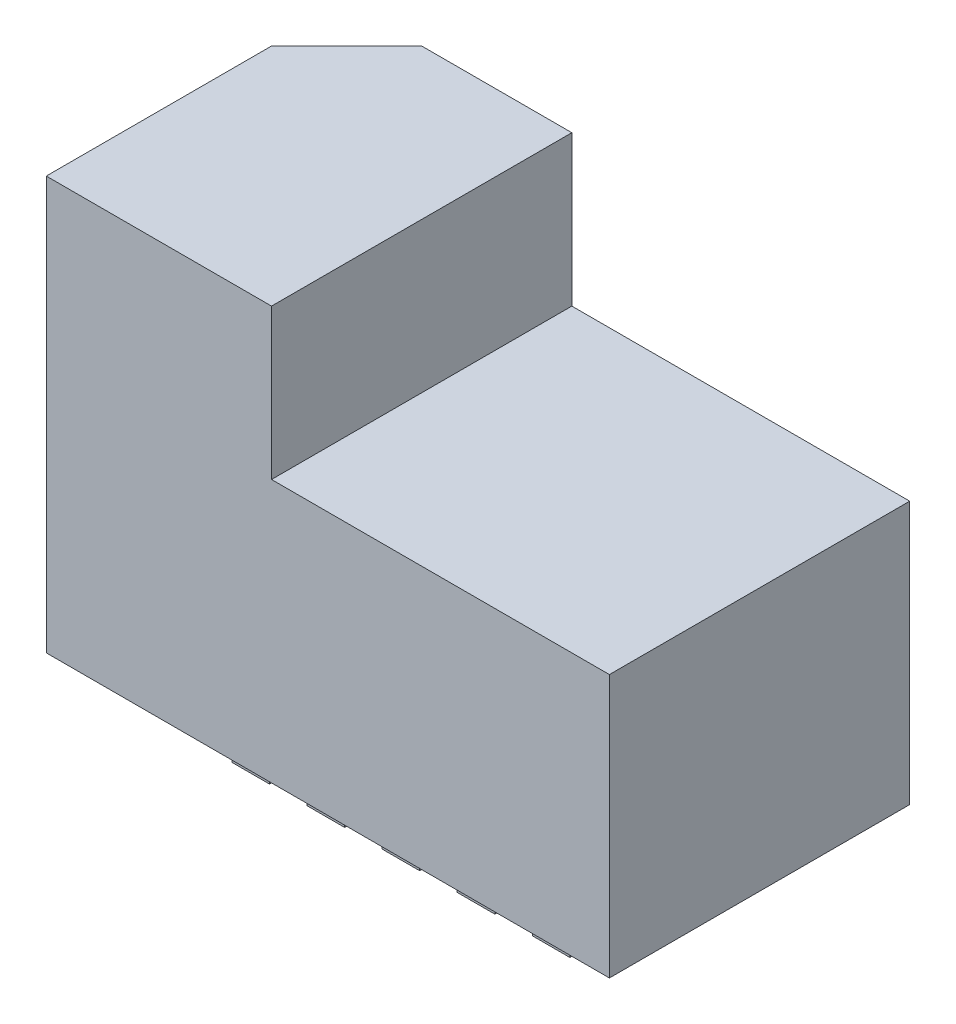
SolidWorks part; units mm, degrees
ref_plane "Front Plane" through (0, 0, 0) normal (0, 0, 1) x (1, 0, 0)
ref_plane "Top Plane" through (0, 0, 0) normal (0, 1, 0) x (1, 0, 0)
ref_plane "Right Plane" through (0, 0, 0) normal (1, 0, 0) x (0, 0, -1)
sketch "Sketch1" plane through (0, 0, 0) normal (0, 1, 0) x (1, 0, 0)
  line L0 (0, 0) -> (38.1, 0)
  line L1 (38.1, 0) -> (38.1, 50.8)
  line L2 (38.1, 50.8) -> (12.7, 50.8)
  line L3 (0, 0) -> (0, 38.1)
  line L4 (0, 38.1) -> (12.7, 50.8)
  dimension "D1" = 38.1
  dimension "D2" = 25.4
  dimension "D3" = 38.1
extrude "Boss-Extrude1" add sketch "Sketch1" along normal blind 69.85
sketch "Sketch2" plane through (38.1, 0, 0) normal (1, 0, 0) x (0, 0, -1)
  line L0 (50.8, 69.85) -> (50.8, 0) construction
  line L1 (0, 0) -> (50.8, 0)
  line L2 (0, 0) -> (0, 44.45)
  line L3 (0, 44.45) -> (50.8, 44.45)
  line L4 (50.8, 0) -> (50.8, 44.45)
  dimension "D1" = 44.45
extrude "Boss-Extrude2" add sketch "Sketch2" along normal blind 57.15
sketch "Sketch3" plane through (0, 0, 0) normal (0, -1, 0) x (-1, 0, 0)
  line L0 (0, 38.1) -> (0, 0) construction
  line L1 (-25.4, 6.0128) -> (-31.75, 6.0128)
  line L2 (-25.4, 6.0128) -> (-25.4, 44.0361)
  line L3 (-25.4, 44.0361) -> (-31.75, 44.0361)
  line L4 (-31.75, 6.0128) -> (-31.75, 44.0361)
  line L5 (-38.1, 6.0128) -> (-44.45, 6.0128)
  line L6 (-38.1, 6.0128) -> (-38.1, 44.0361)
  line L7 (-38.1, 44.0361) -> (-44.45, 44.0361)
  line L8 (-44.45, 6.0128) -> (-44.45, 44.0361)
  line L9 (-50.8, 6.0128) -> (-57.15, 6.0128)
  line L10 (-50.8, 6.0128) -> (-50.8, 44.0361)
  line L11 (-50.8, 44.0361) -> (-57.15, 44.0361)
  line L12 (-57.15, 6.0128) -> (-57.15, 44.0361)
  line L13 (-63.5, 6.0128) -> (-69.85, 6.0128)
  line L14 (-63.5, 6.0128) -> (-63.5, 44.0361)
  line L15 (-63.5, 44.0361) -> (-69.85, 44.0361)
  line L16 (-69.85, 6.0128) -> (-69.85, 44.0361)
  line L17 (-76.2, 6.0128) -> (-82.55, 6.0128)
  line L18 (-76.2, 6.0128) -> (-76.2, 44.0361)
  line L19 (-76.2, 44.0361) -> (-82.55, 44.0361)
  line L20 (-82.55, 6.0128) -> (-82.55, 44.0361)
  dimension "D1" = 6.35
  dimension "D2" = 25.4
  dimension "D3" = 6.35
  dimension "D4" = 6.35
  dimension "D5" = 6.35
  dimension "D6" = 6.35
  dimension "D7" = 6.35
  dimension "D8" = 6.35
  dimension "D9" = 6.35
  dimension "D10" = 6.35
extrude "Boss-Extrude3" add sketch "Sketch3" along normal blind 6.35
